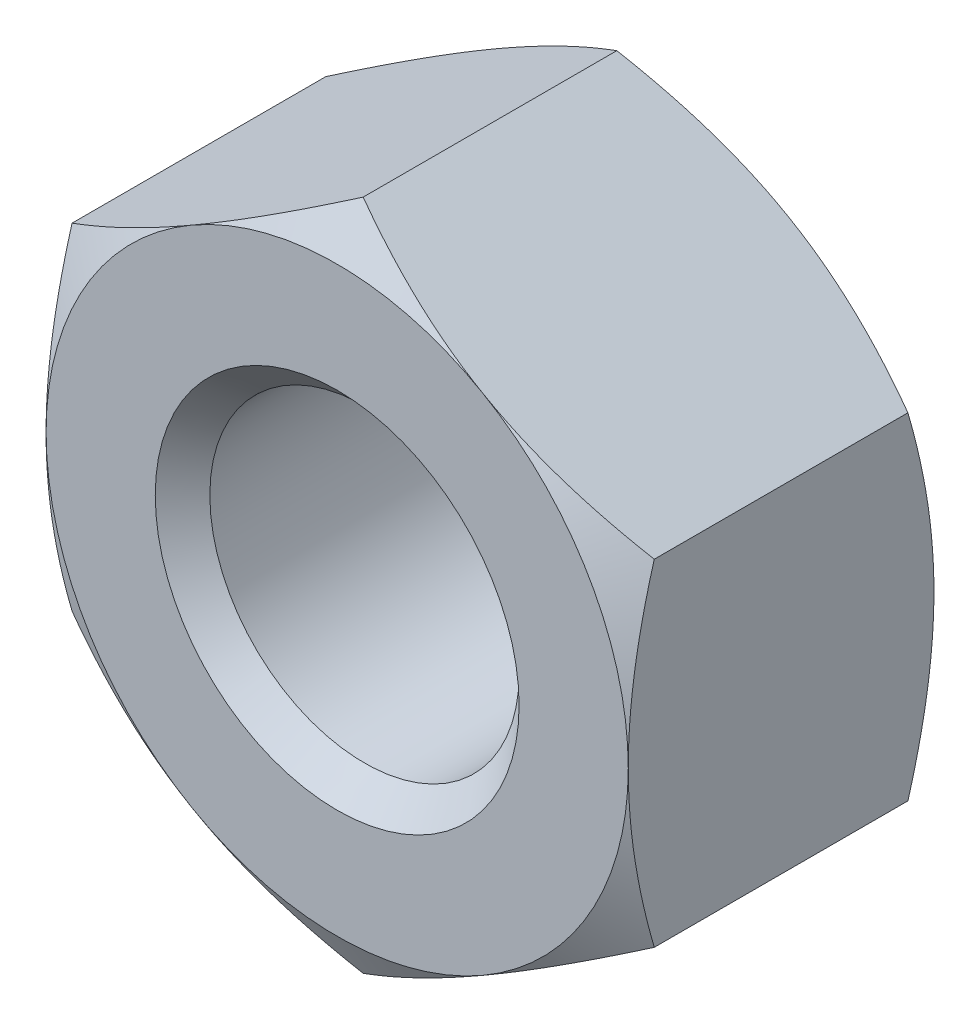
SolidWorks part; units mm, degrees
ref_plane "Front Plane" through (0, 0, 0) normal (0, 0, 1) x (1, 0, 0)
ref_plane "Top Plane" through (0, 0, 0) normal (0, 1, 0) x (1, 0, 0)
ref_plane "Right Plane" through (0, 0, 0) normal (1, 0, 0) x (0, 0, -1)
sketch "Sketch1" plane through (0, 0, 0) normal (0, 0, 1) x (1, 0, 0)
  line L1 (0, 9.2376) -> (-8, 4.6188)
  line L2 (-8, 4.6188) -> (-8, -4.6188)
  line L3 (-8, -4.6188) -> (0, -9.2376)
  line L4 (0, -9.2376) -> (8, -4.6188)
  line L5 (8, -4.6188) -> (8, 4.6188)
  line L6 (8, 4.6188) -> (0, 9.2376)
  circle A0 centre (0, 0) radius 8 construction
  circle A1 centre (0, 0) radius 4.25
  dimension "D2" = 8.5
  dimension "D1" = 16
extrude "Boss-Extrude1" add sketch "Sketch1" along normal mid plane 8.4
sketch "Sketch3" plane through (8, 0, 0) normal (1, 0, 0) x (0, 0, -1)
  line L0 (0, 0) -> (4.2, 0) construction
  line L1 (4.2, -4.6188) -> (4.2, 4.6188) construction
  line L2 (3.2436, 4.6188) -> (4.2, 2.9623)
  line L3 (-4.2, 4.6188) -> (4.2, 4.6188) construction
  line L4 (3.2436, 4.6188) -> (4.2, 4.6188)
  line L5 (4.2, 4.6188) -> (4.2, 2.9623)
  dimension "D1" = 30
sketch "Sketch4" plane through (0, 0, 0) normal (1, 0, 0) x (0, 0, -1)
  line L0 (3.4855, 9.2376) -> (4.2, 8)
  line L1 (-4.2, 9.2376) -> (4.2, 9.2376) construction
  line L2 (4.2, 4.6188) -> (4.2, 9.2376) construction
  line L3 (4.2, 8) -> (4.2, 9.2376)
  line L4 (0, 0) -> (9.3285, 0) construction
  line L5 (3.4855, 9.2376) -> (4.2, 9.2376)
  dimension "D1" = 8
  dimension "D2" = 30
revolve "Cut-Revolve5" cut sketch "Sketch4" angle 360 about L4
sketch "Sketch5" plane through (0, 0, 0) normal (1, 0, 0) x (0, 0, -1)
  line L0 (0, 0) -> (-6.6661, 0) construction
  line L1 (-3.4855, 9.2376) -> (-4.2, 8)
  line L2 (-4.2, 9.2376) -> (3.4855, 9.2376) construction
  line L3 (-4.2, 4.6188) -> (-4.2, 9.2376) construction
  line L4 (-3.4855, 9.2376) -> (-4.2, 9.2376)
  line L5 (-4.2, 9.2376) -> (-4.2, 8)
  dimension "D1" = 8
  dimension "D2" = 30
revolve "Cut-Revolve6" cut sketch "Sketch5" angle 360 about L0
chamfer "Chamfer1" distance 0.75 angle 45 2 edges at (4.25, 0, 4.2) (4.25, 0, -4.2)
cosmetic thread "Cosmetic Thread1" parameters "D2"=10
cosmetic thread "Cosmetic Thread2" parameters "D2"=10
